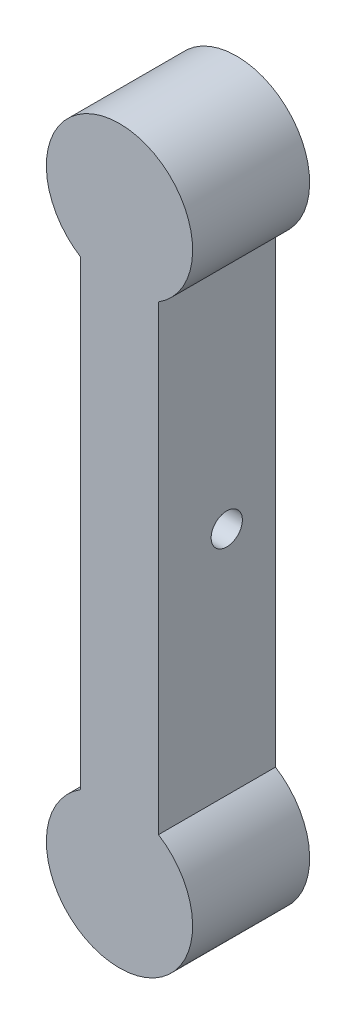
SolidWorks part; units mm, degrees
material "ABS"
ref_plane "Plano frontal" through (0, 0, 0) normal (0, 0, 1) x (1, 0, 0)
ref_plane "Plano superior" through (0, 0, 0) normal (0, 1, 0) x (1, 0, 0)
ref_plane "Plano direito" through (0, 0, 0) normal (1, 0, 0) x (0, 0, -1)
sketch "Esboço1" plane through (0, 0, 0) normal (0, 0, 1) x (1, 0, 0)
  line L0 (4, 53.6557) -> (4, 6.3443)
  line L1 (0, 60) -> (0, 0) construction
  line L7 (-4, 53.6557) -> (-4, 6.3443)
  circle A0 centre (0, 60) radius 4
  circle A1 centre (0, 0) radius 4
  arc A2 (4, 53.6557) -> (-4, 53.6557) centre (0, 60) ccw
  arc A3 (-4, 6.3443) -> (4, 6.3443) centre (0, 0) ccw
  point P4 (5.3934, 54.7883)
  point P6 (0, 0)
  point P14 (-9.5, 38)
  dimension "D1" = 8
  dimension "D2" = 15
  dimension "D3" = 60
  dimension "D4" = 8
extrude "Ressalto-extrusão1" add sketch "Esboço1" along normal blind 10
sketch "Esboço2" plane through (-4, 0, 0) normal (-1, 0, 0) x (0, 0, 1)
  line L0 (0, 30) -> (10, 30) construction
  line L1 (0, 53.6557) -> (0, 6.3443) construction
  line L2 (10, 53.6557) -> (10, 6.3443) construction
  circle A0 centre (5, 30) radius 1.6
  dimension "D1" = 3.2
extrude "Corte-extrusão1" cut sketch "Esboço2" against normal blind 10 contours A0
sketch "Esboço3" plane through (0, 0, 10) normal (0, 0, 1) x (1, 0, 0)
  line L2 (-4, 53.6557) -> (-4, 6.3443)
  line L4 (4, 53.6557) -> (4, 6.3443)
  arc A0 (4, 53.6557) -> (-4, 53.6557) centre (0, 60) ccw
  arc A1 (-4, 6.3443) -> (4, 6.3443) centre (0, 0) ccw
extrude "Ressalto-extrusão2" add sketch "Esboço3" along normal blind 2
